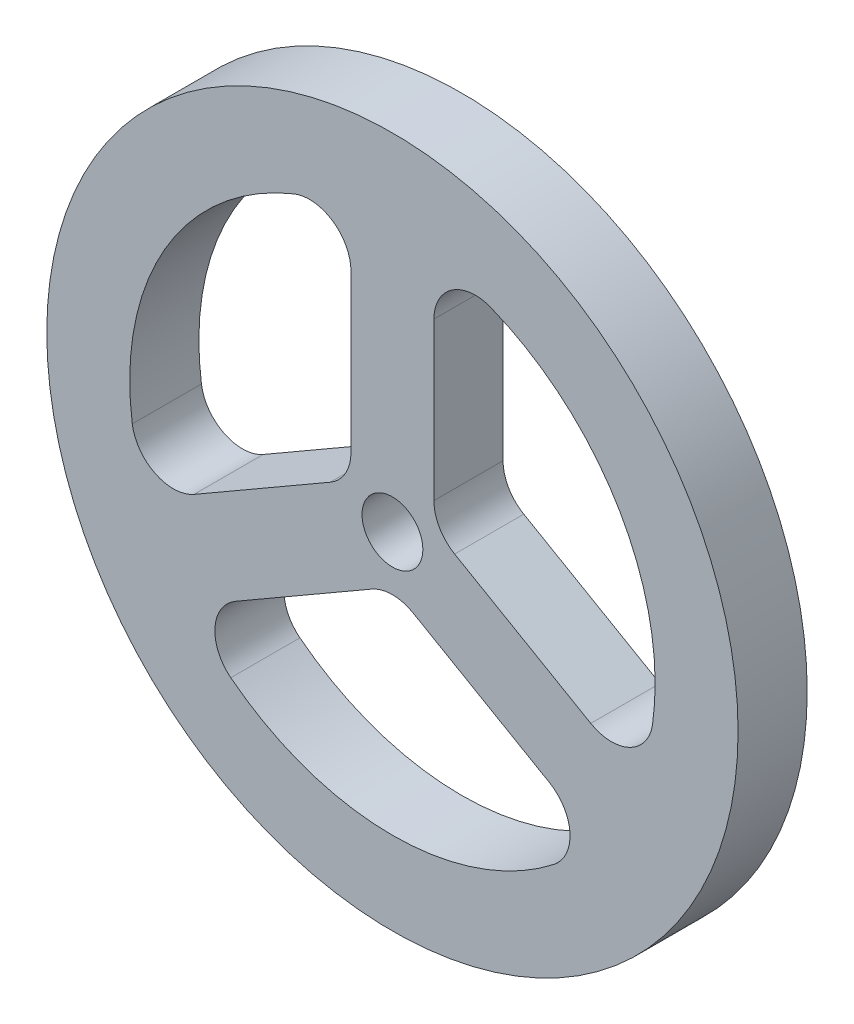
SolidWorks part; units mm, degrees
material "ABS"
ref_plane "Front Plane" through (0, 0, 0) normal (0, 0, 1) x (1, 0, 0)
ref_plane "Top Plane" through (0, 0, 0) normal (0, 1, 0) x (1, 0, 0)
ref_plane "Right Plane" through (0, 0, 0) normal (1, 0, 0) x (0, 0, -1)
sketch "Sketch1" plane through (0, 0, 0) normal (0, 0, 1) x (1, 0, 0)
  line L0 (0, 0) -> (0, 24.13) construction
  line L1 (0, 0) -> (20.8972, -12.065) construction
  line L2 (0, 0) -> (-20.8972, -12.065) construction
  line L3 (-3.81, 2.1997) -> (-22.8022, -8.7654)
  line L4 (0, -4.3994) -> (18.9922, -15.3646)
  line L5 (3.81, 2.1997) -> (3.81, 24.13)
  line L6 (0, -4.3994) -> (-18.9922, -15.3646)
  line L7 (3.81, 2.1997) -> (22.8022, -8.7654)
  line L8 (-3.81, 2.1997) -> (-3.81, 24.13)
  line L9 (1.905, 3.2996) -> (22.8022, -8.7654) construction
  line L10 (3.81, 0) -> (3.81, 24.13) construction
  line L11 (-1.905, 3.2996) -> (-22.8022, -8.7654) construction
  line L12 (-3.81, 0) -> (-3.81, 24.13) construction
  line L13 (-1.905, -3.2996) -> (18.9922, -15.3646) construction
  line L14 (1.905, -3.2996) -> (-18.9922, -15.3646) construction
  circle A0 centre (0, 0) radius 31.75
  circle A1 centre (0, 0) radius 2.794
  arc A3 (-18.7301, -15.2132) -> (18.7301, -15.2132) centre (0, 0) ccw
  arc A4 (22.5401, -8.6141) -> (3.81, 23.8273) centre (0, 0) ccw
  arc A5 (-3.81, 23.8273) -> (-22.5401, -8.6141) centre (0, 0) ccw
  point P12 (0, 0)
  dimension "D1" = 63.5
  dimension "D2" = 5.588
  dimension "D3" = 7.62
  dimension "D5" = 3.81
  dimension "D6" = 3.81
  dimension "D4" = 3
extrude "Boss-Extrude3" add sketch "Sketch1" along normal blind 6.35
fillet "Fillet1" radius 3.81 9 edges at (0, -4.3994, 3.175) (-18.7301, -15.2132, 3.175) (3.81, 23.8273, 3.175) (3.81, 2.1997, 3.175) (-22.5401, -8.6141, 3.175) (-3.81, 2.1997, 3.175) (-3.81, 23.8273, 3.175) (18.7301, -15.2132, 3.175) (22.5401, -8.6141, 3.175)
equation "\"rodThick\"= 0.085in"
equation "\"clear\"= 0.003in"
